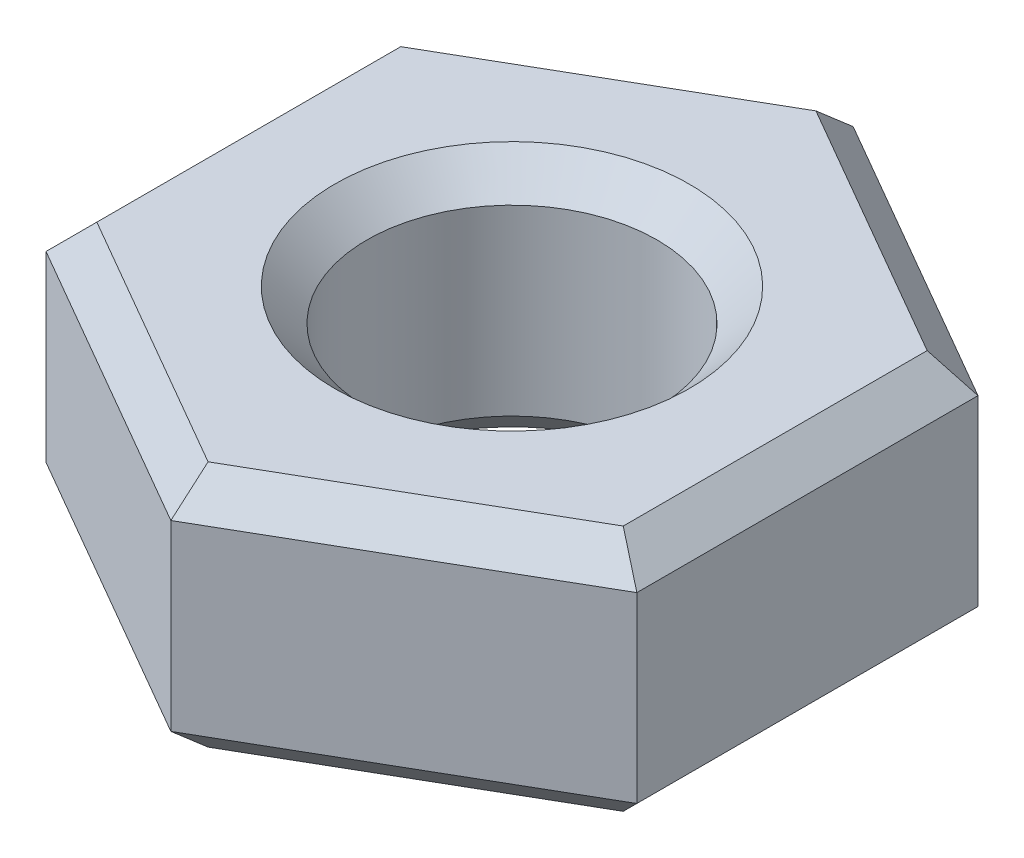
SolidWorks part; units mm, degrees
ref_plane "Front Plane" through (0, 0, 0) normal (0, 0, 1) x (1, 0, 0)
ref_plane "Top Plane" through (0, 0, 0) normal (0, 1, 0) x (1, 0, 0)
ref_plane "Right Plane" through (0, 0, 0) normal (1, 0, 0) x (0, 0, -1)
sketch "Sketch1" plane through (0, 0, 0) normal (0, 1, 0) x (1, 0, 0)
  line L0 (0, 0) -> (0, 6.1868) construction
  line L1 (2.75, -1.5877) -> (2.75, 1.5877)
  line L2 (2.75, 1.5877) -> (0, 3.1754)
  line L3 (0, 3.1754) -> (-2.75, 1.5877)
  line L4 (-2.75, 1.5877) -> (-2.75, -1.5877)
  line L5 (-2.75, -1.5877) -> (0, -3.1754)
  line L6 (0, -3.1754) -> (2.75, -1.5877)
  line L7 (0, 0) -> (2.75, 0) construction
  circle A0 centre (0, 0) radius 2.75 construction
  circle A1 centre (0, 0) radius 1.35
  dimension "D1" = 5.5
  dimension "D2" = 2.7
  dimension "D3" = 90
extrude "Boss-Extrude1" add sketch "Sketch1" along normal blind 2.3
chamfer "Chamfer1" distance 0.3 angle 45 14 edges at (0, 0, 1.35) (2.75, 0, 0) (1.375, 0, -2.3816) (-1.375, 0, -2.3816) (-2.75, 0, 0) (-1.375, 0, 2.3816) (1.375, 0, 2.3816) (0, 2.3, 1.35) (-1.375, 2.3, 2.3816) (-2.75, 2.3, 0) (-1.375, 2.3, -2.3816) (1.375, 2.3, -2.3816) (2.75, 2.3, 0) (1.375, 2.3, 2.3816)
